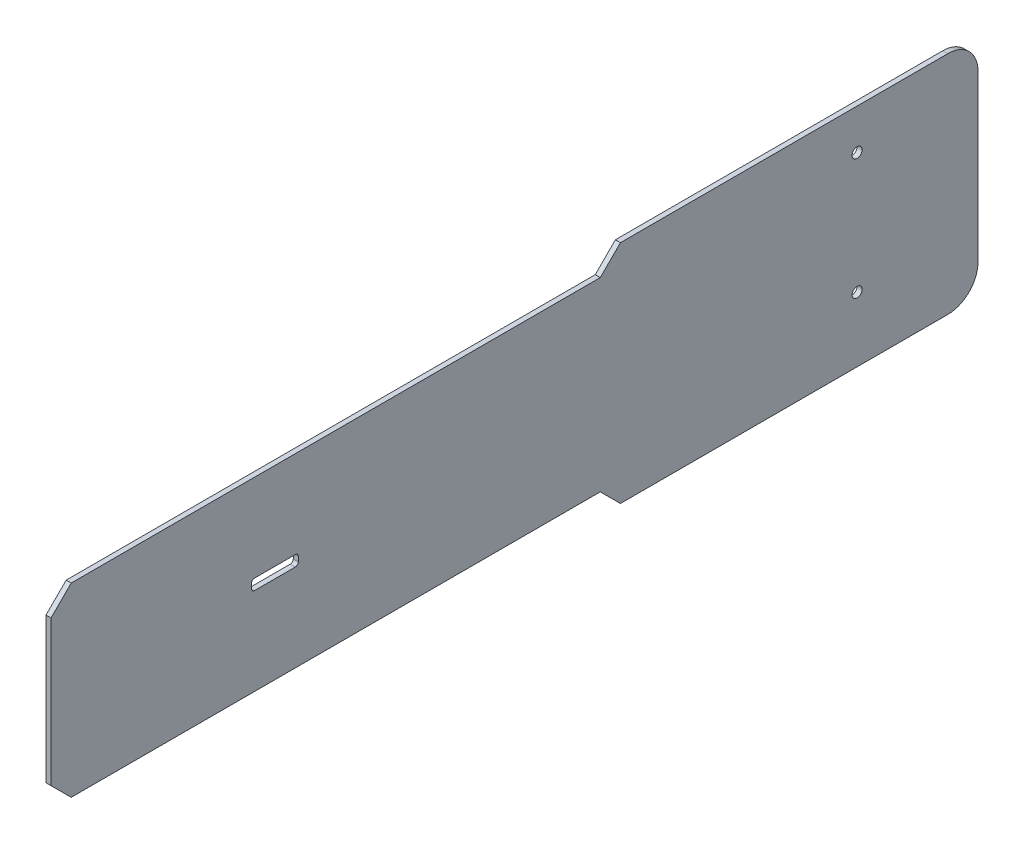
SolidWorks part; units mm, degrees
ref_plane "Front Plane" through (0, 0, 0) normal (0, 0, 1) x (1, 0, 0)
ref_plane "Top Plane" through (0, 0, 0) normal (0, 1, 0) x (1, 0, 0)
ref_plane "Right Plane" through (0, 0, 0) normal (1, 0, 0) x (0, 0, -1)
sketch "Sketch2" plane through (0, 0, 0) normal (-1, 0, 0) x (0, 1, 0)
  line L1 (-55.0231, 28.6615) -> (-32.6031, 28.6615)
  line L2 (-55.0231, 28.6615) -> (-55.0231, -63.3385)
  line L3 (-55.0231, -63.3385) -> (-32.6031, -63.3385)
  line L4 (-32.6031, 28.6615) -> (-32.6031, -63.3385)
  dimension "D1" = 92
  dimension "D2" = 22.42
extrude "Boss-Extrude2" add sketch "Sketch2" along normal blind 0.5 contours L2 L3 L4 L1
fillet "Fillet4" radius 3 1 edges at (-0.25, -55.0231, -28.6615)
fillet "Fillet7" radius 3 1 edges at (-0.25, -32.6031, -28.6615)
sketch "Sketch4" plane through (-0.5, 0, 0) normal (-1, 0, 0) x (0, 1, 0)
  line L0 (-55.0231, 25.6615) -> (-55.0231, -63.3385) construction
  line L1 (-55.0231, -8.8285) -> (-53.0231, -8.8285)
  line L2 (-55.0231, -8.8285) -> (-55.0231, -63.3385)
  line L3 (-55.0231, -63.3385) -> (-53.0231, -63.3385)
  line L4 (-53.0231, -8.8285) -> (-53.0231, -63.3385)
  line L5 (-55.0231, -63.3385) -> (-32.6031, -63.3385) construction
  dimension "D1" = 2
  dimension "D2" = 54.51
extrude "Cut-Extrude1" cut sketch "Sketch4" against normal blind 0.5
sketch "Sketch5" plane through (-0.5, 0, 0) normal (-1, 0, 0) x (0, 1, 0)
  line L1 (-34.6031, -8.8285) -> (-32.6031, -8.8285)
  line L2 (-34.6031, -8.8285) -> (-34.6031, -63.3385)
  line L3 (-34.6031, -63.3385) -> (-32.6031, -63.3385)
  line L4 (-32.6031, -8.8285) -> (-32.6031, -63.3385)
  dimension "D1" = 2
  dimension "D2" = 54.51
extrude "Cut-Extrude2" cut sketch "Sketch5" against normal blind 0.5
sketch "Sketch6" plane through (-0.5, 0, 0) normal (-1, 0, 0) x (0, 1, 0)
  line L0 (-53.0231, -63.3385) -> (-53.0231, -61.3385)
  line L1 (-53.0231, -63.3385) -> (-53.0231, -8.8285) construction
  line L2 (-53.0231, -63.3385) -> (-51.0231, -63.3385)
  line L3 (-53.0231, -63.3385) -> (-34.6031, -63.3385) construction
  line L4 (-53.0231, -61.3385) -> (-51.0231, -63.3385)
extrude "Cut-Extrude3" cut sketch "Sketch6" against normal blind 0.5
sketch "Sketch7" plane through (-0.5, 0, 0) normal (-1, 0, 0) x (0, 1, 0)
  line L0 (-34.6031, -63.3385) -> (-34.6031, -61.3385)
  line L1 (-34.6031, -8.8285) -> (-34.6031, -63.3385) construction
  line L2 (-34.6031, -63.3385) -> (-36.6031, -63.3385)
  line L3 (-51.0231, -63.3385) -> (-34.6031, -63.3385) construction
  line L4 (-34.6031, -61.3385) -> (-36.6031, -63.3385)
extrude "Cut-Extrude4" cut sketch "Sketch7" against normal blind 0.5
sketch "Sketch8" plane through (-0.5, 0, 0) normal (-1, 0, 0) x (0, 1, 0)
  line L0 (-53.0231, -8.8285) -> (-55.0231, -8.8285)
  line L2 (-55.0231, -8.8285) -> (-55.0231, -6.8285)
  line L3 (-55.0231, 25.6615) -> (-55.0231, -8.8285) construction
  line L4 (-55.0231, -6.8285) -> (-53.0231, -8.8285)
extrude "Cut-Extrude7" cut sketch "Sketch8" against normal blind 0.5
sketch "Sketch9" plane through (-0.5, 0, 0) normal (-1, 0, 0) x (0, 1, 0)
  line L0 (-34.6031, -8.8285) -> (-32.6031, -8.8285)
  line L1 (-32.6031, -8.8285) -> (-34.6031, -8.8285) construction
  line L2 (-32.6031, -8.8285) -> (-32.6031, -6.8285)
  line L3 (-32.6031, 25.6615) -> (-32.6031, -8.8285) construction
  line L4 (-32.6031, -6.8285) -> (-34.6031, -8.8285)
extrude "Cut-Extrude8" cut sketch "Sketch9" against normal blind 0.5
sketch "Sketch11" plane through (-0.5, 0, 0) normal (-1, 0, 0) x (0, 1, 0)
  line L3 (-44.3481, -38.7985) -> (-43.2781, -38.7985)
  line L4 (-44.3481, -38.7985) -> (-44.3481, -43.4385)
  line L5 (-44.3481, -43.4385) -> (-43.2781, -43.4385)
  line L6 (-43.2781, -38.7985) -> (-43.2781, -43.4385)
extrude "Cut-Extrude9" cut sketch "Sketch11" against normal blind 0.5
fillet "Fillet8" radius 0.3 1 edges at (-0.25, -44.3481, 38.7985)
fillet "Fillet9" radius 0.3 1 edges at (-0.25, -43.2781, 38.7985)
fillet "Fillet10" radius 0.3 1 edges at (-0.25, -43.2781, 43.4385)
fillet "Fillet11" radius 0.3 1 edges at (-0.25, -44.3481, 43.4385)
sketch "Sketch12" plane through (-0.5, 0, 0) normal (-1, 0, 0) x (0, 1, 0)
  line L1 (-43.8131, -38.7985) -> (-43.8131, -6.1533)
  line L2 (-43.5781, -38.7985) -> (-44.0481, -38.7985) construction
  line L4 (-43.8131, -43.4385) -> (-43.8131, -49.5691)
  line L5 (-44.0481, -43.4385) -> (-43.5781, -43.4385) construction
  circle A0 centre (-49.1163, 16.6615) radius 0.5
  circle A1 centre (-36.6031, 16.6615) radius 0.5
extrude "Cut-Extrude11" cut sketch "Sketch12" against normal blind 0.5 contours A1
sketch "Sketch13" plane through (-0.5, 0, 0) normal (-1, 0, 0) x (0, 1, 0)
  circle A0 centre (-48.6031, 16.6615) radius 0.5
extrude "Cut-Extrude12" cut sketch "Sketch13" against normal blind 5
sketch "Sketch25" plane through (-0.5, 0, 0) normal (-1, 0, 0) x (0, 1, 0)
  line L0 (-36.5927, 3.2864) -> (-43.6947, -2.8562)
  line L2 (-36.5443, 16.8519) -> (-36.6843, 16.8519)
  line L3 (-36.5443, 16.8519) -> (-36.5443, 3.3923)
  line L5 (-36.6843, 16.8519) -> (-36.6843, 3.4563)
  line L8 (-43.8831, -2.898) -> (-43.8831, -52.2135)
  line L10 (-43.7431, -2.962) -> (-43.7431, -52.2135)
  line L12 (-36.7327, 3.3504) -> (-43.8347, -2.7921)
  line L14 (-48.6731, 16.6465) -> (-48.5331, 16.6465)
  line L15 (-48.6731, 16.6465) -> (-48.6731, -52.2135)
  line L17 (-48.5331, 16.6465) -> (-48.5331, -52.2135)
  arc A0 (-43.7431, -2.962) -> (-43.6947, -2.8562) centre (-43.6031, -2.962) cw
  arc A1 (-43.8831, -2.898) -> (-43.8347, -2.7921) centre (-43.7431, -2.898) cw
  arc A2 (-36.5927, 3.2864) -> (-36.5443, 3.3923) centre (-36.6843, 3.3923) ccw
  arc A3 (-36.6843, 3.4563) -> (-36.7327, 3.3504) centre (-36.8243, 3.4563) cw
  arc A4 (-48.5331, -52.2135) -> (-43.8831, -52.2135) centre (-46.2081, -52.2135) ccw
  arc A5 (-48.6731, -52.2135) -> (-43.7431, -52.2135) centre (-46.2081, -52.2135) ccw
  dimension "D1" = 0.14
  dimension "D2" = 0.14
  dimension "D3" = 0.14
  dimension "D4" = 0.14
extrude "Cut-Extrude24" cut sketch "Sketch25" against normal blind 0.07 draft 44
sketch "Sketch26" plane through (-0.5, 0, 0) normal (-1, 0, 0) x (0, 1, 0)
sketch "Sketch27" plane through (-0.5, 0, 0) normal (-1, 0, 0) x (0, 1, 0)
sketch "Sketch28" plane through (-0.5, 0, 0) normal (-1, 0, 0) x (0, 1, 0)
sketch "Sketch29" plane through (-0.5, 0, 0) normal (-1, 0, 0) x (0, 1, 0)
sketch "Sketch30" plane through (-0.5, 0, 0) normal (-1, 0, 0) x (0, 1, 0)
